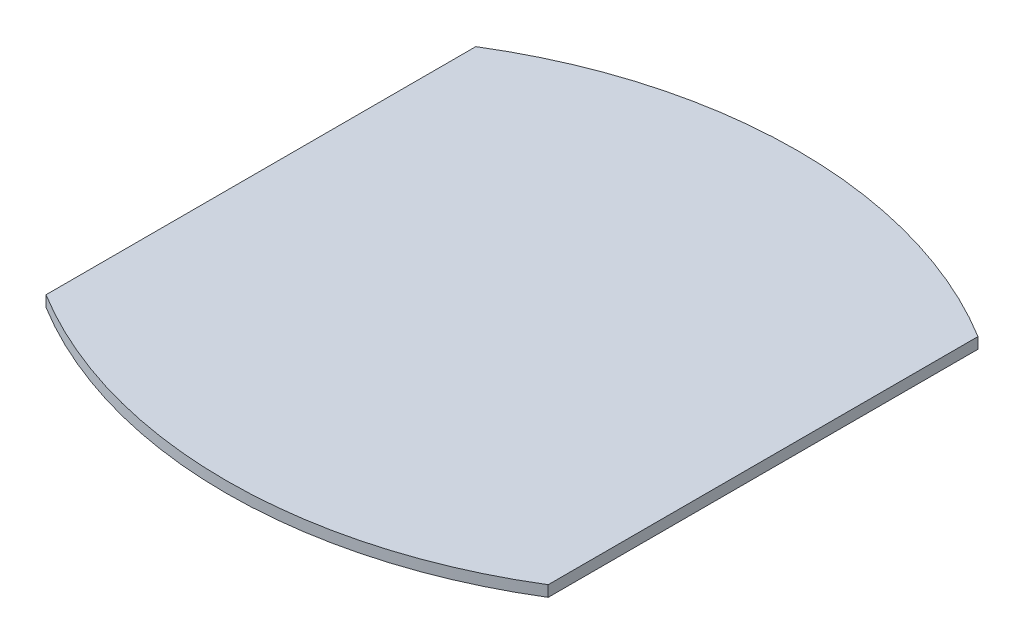
SolidWorks part; units mm, degrees
ref_plane "Plan de face" through (0, 0, 0) normal (0, 0, 1) x (1, 0, 0)
ref_plane "Plan de dessus" through (0, 0, 0) normal (0, 1, 0) x (1, 0, 0)
ref_plane "Plan de droite" through (0, 0, 0) normal (1, 0, 0) x (0, 0, -1)
sketch "Esquisse1" plane through (0, 0, 0) normal (0, 1, 0) x (1, 0, 0)
  line L0 (-145, 0) -> (0, 0) construction
  line L1 (-145, -124.1036) -> (145, -124.1036)
  line L2 (-145, -124.1036) -> (-145, 124.1036)
  line L3 (-145, 124.1036) -> (145, 124.1036)
  line L4 (145, -124.1036) -> (145, 124.1036)
  line L5 (-145, -124.1036) -> (145, 124.1036) construction
  line L6 (-145, 124.1036) -> (145, -124.1036) construction
  line L11 (0, 0) -> (0, -275) construction
  arc A0 (-145, 124.1036) -> (145, 124.1036) centre (0, -112.5) cw
  arc A1 (-145, -124.1036) -> (145, -124.1036) centre (0, 112.5) ccw
  point P0 (0, 0)
  point P19 (0, 165)
  point P20 (0, -165)
  dimension "D3" = 277.5
  dimension "D4" = 277.5
  dimension "D1" = 290
  dimension "D2" = 330
extrude "Boss.-Extru.1" add sketch "Esquisse1" along normal blind 6.35
